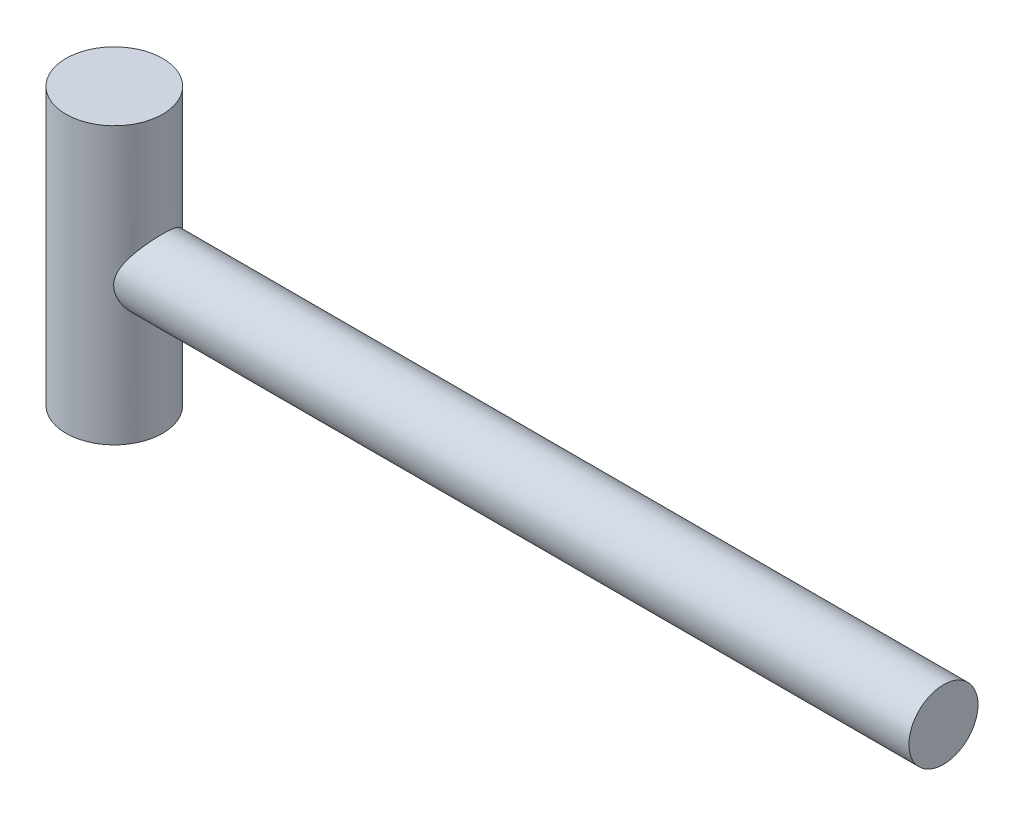
SolidWorks part; units mm, degrees
ref_plane "Front Plane" through (0, 0, 0) normal (0, 0, 1) x (1, 0, 0)
ref_plane "Top Plane" through (0, 0, 0) normal (0, 1, 0) x (1, 0, 0)
ref_plane "Right Plane" through (0, 0, 0) normal (1, 0, 0) x (0, 0, -1)
sketch "Sketch3" plane through (0, 0, 0) normal (0, 1, 0) x (1, 0, 0)
  circle A0 centre (0, 0) radius 1.75
  dimension "D1" = 3.5
extrude "Boss-Extrude1" add sketch "Sketch3" along normal mid plane 10
sketch "Sketch4" plane through (0, 0, 0) normal (1, 0, 0) x (0, 0, -1)
  circle A0 centre (0, 0) radius 1.25
  dimension "D1" = 2.5
extrude "Boss-Extrude2" add sketch "Sketch4" along normal blind 30 contours A0
